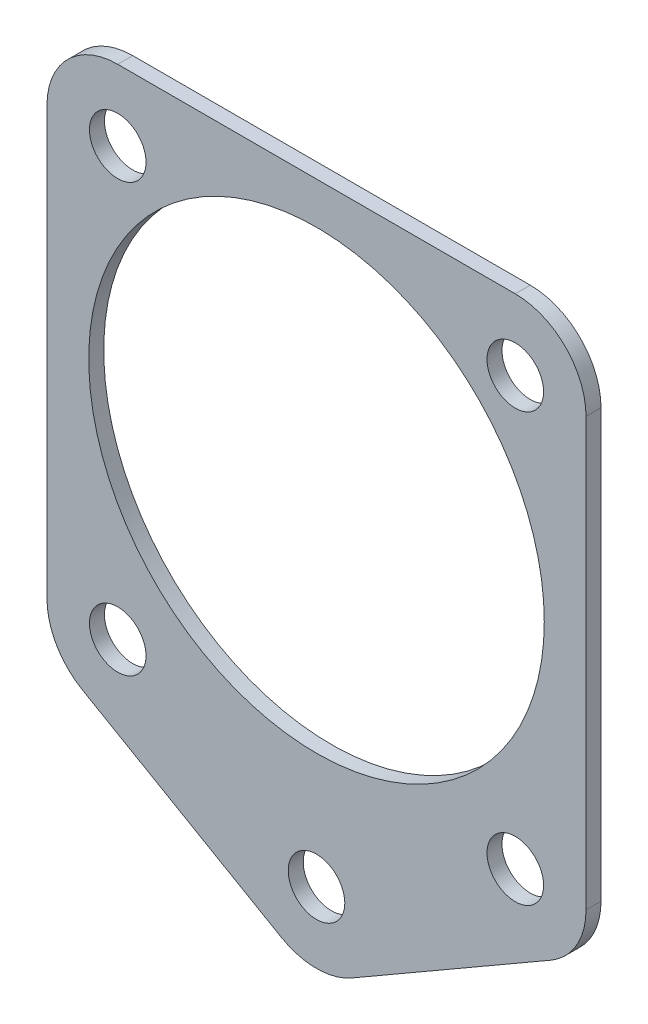
SolidWorks part; units mm, degrees
material "POLYURETHANE (11671)"
ref_plane "Front Plane" through (0, 0, 0) normal (0, 0, 1) x (1, 0, 0)
ref_plane "Top Plane" through (0, 0, 0) normal (0, 1, 0) x (1, 0, 0)
ref_plane "Right Plane" through (0, 0, 0) normal (1, 0, 0) x (0, 0, -1)
sketch "Sketch1" plane through (0, 0, 0) normal (0, 0, 1) x (1, 0, 0)
  line L0 (0, 0) -> (48.387, 0) construction
  line L1 (48.387, 3.6662) -> (48.387, 42.037)
  line L2 (42.037, 48.387) -> (6.35, 48.387)
  line L3 (0, 42.037) -> (0, 3.6662)
  line L4 (3.175, -1.8331) -> (21.0185, -12.135)
  line L5 (27.3685, -12.135) -> (45.212, -1.8331)
  arc A0 (0, 3.6662) -> (3.175, -1.8331) centre (6.35, 3.6662) ccw
  arc A1 (21.0185, -12.135) -> (27.3685, -12.135) centre (24.1935, -6.6358) ccw
  arc A2 (45.212, -1.8331) -> (48.387, 3.6662) centre (42.037, 3.6662) ccw
  arc A3 (48.387, 42.037) -> (42.037, 48.387) centre (42.037, 42.037) ccw
  arc A4 (6.35, 48.387) -> (0, 42.037) centre (6.35, 42.037) ccw
  circle A5 centre (6.35, 42.037) radius 2.54
  circle A6 centre (42.037, 42.037) radius 2.54
  circle A7 centre (42.037, 3.6662) radius 2.54
  circle A8 centre (6.35, 3.6662) radius 2.54
  circle A9 centre (24.1935, -6.6358) radius 2.54
  circle A10 centre (24.1935, 24.1935) radius 20.447
  point P16 (48.387, 48.387)
  dimension "D5" = 6.35
  dimension "D6" = 5.08
  dimension "D7" = 40.894
  dimension "D1" = 48.387
  dimension "D2" = 48.387
  dimension "D3" = 30
  dimension "D4" = 30
  dimension "D8" = 24.1935
  dimension "D9" = 24.1935
extrude "Boss-Extrude1" add sketch "Sketch1" along normal blind 1.3462
